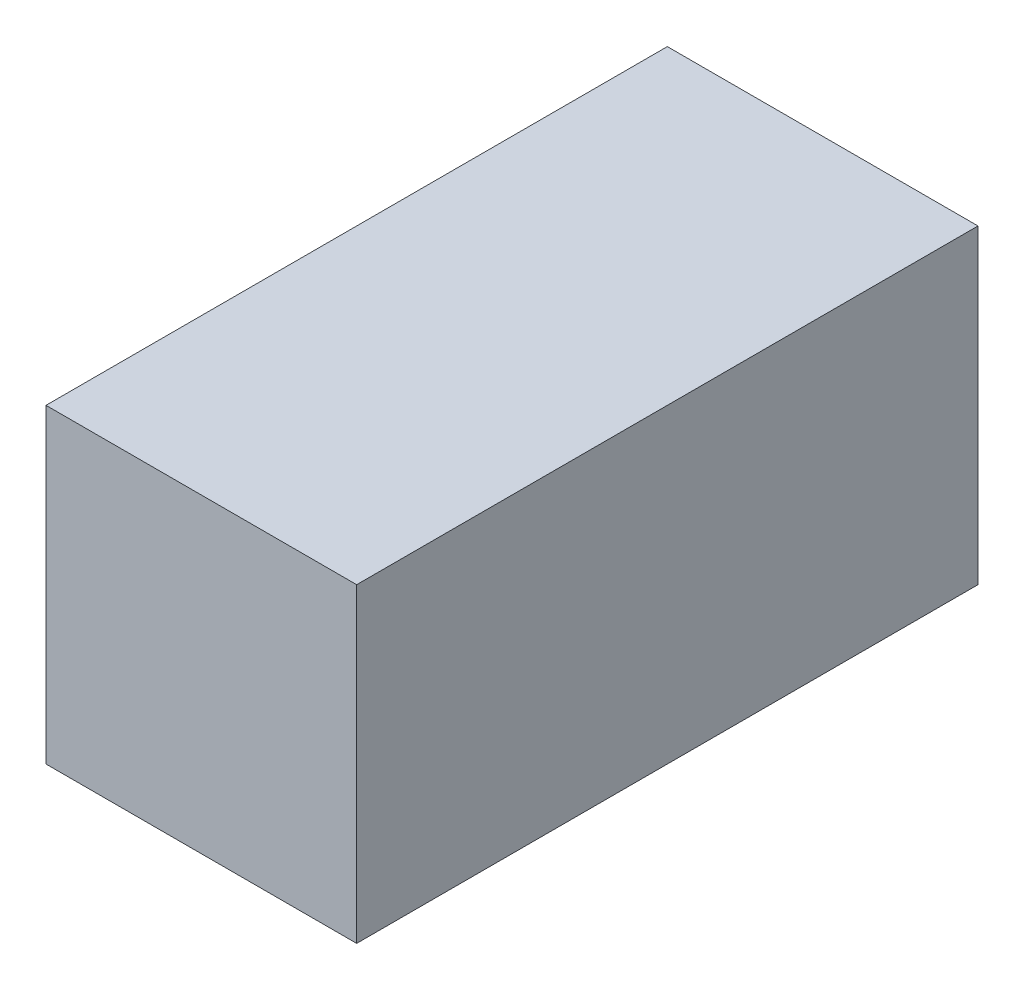
SolidWorks part; units mm, degrees
ref_plane "Front Plane" through (0, 0, 0) normal (0, 0, 1) x (1, 0, 0)
ref_plane "Top Plane" through (0, 0, 0) normal (0, 1, 0) x (1, 0, 0)
ref_plane "Right Plane" through (0, 0, 0) normal (1, 0, 0) x (0, 0, -1)
sketch "Sketch1" plane through (0, 0, 0) normal (0, 1, 0) x (1, 0, 0)
  line L1 (25, -50) -> (-25, -50)
  line L2 (25, -50) -> (25, 50)
  line L3 (25, 50) -> (-25, 50)
  line L4 (-25, -50) -> (-25, 50)
  line L5 (25, -50) -> (-25, 50) construction
  line L6 (25, 50) -> (-25, -50) construction
  point P0 (0, 0)
  dimension "D1" = 100
  dimension "D2" = 50
extrude "Boss-Extrude1" add sketch "Sketch1" along normal blind 50
